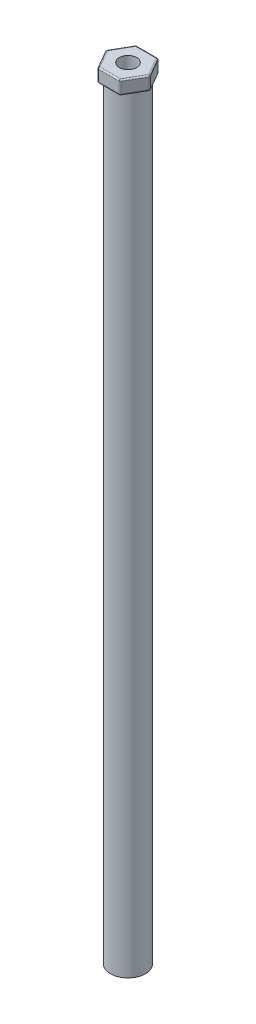
SolidWorks part; units mm, degrees
ref_plane "Front Plane" through (0, 0, 0) normal (0, 0, 1) x (1, 0, 0)
ref_plane "Top Plane" through (0, 0, 0) normal (0, 1, 0) x (1, 0, 0)
ref_plane "Right Plane" through (0, 0, 0) normal (1, 0, 0) x (0, 0, -1)
sketch "Sketch1" plane through (0, 0, 0) normal (0, 1, 0) x (1, 0, 0)
  circle A0 centre (0, 0) radius 6.35
  circle A1 centre (0, 0) radius 3.175
  dimension "D1" = 12.7
extrude "Boss-Extrude1" add sketch "Sketch1" along normal blind 279.4
ref_plane "Plane1" through (0, 139.7, 0) normal (0, 1, 0) x (1, 0, 0)
sketch "Sketch2" plane through (0, 279.4, 0) normal (0, 1, 0) x (1, 0, 0)
  line L1 (-8.0656, 0) -> (-4.0328, -6.985)
  line L2 (-4.0328, -6.985) -> (4.0328, -6.985)
  line L3 (4.0328, -6.985) -> (8.0656, 0)
  line L4 (8.0656, 0) -> (4.0328, 6.985)
  line L5 (4.0328, 6.985) -> (-4.0328, 6.985)
  line L6 (-4.0328, 6.985) -> (-8.0656, 0)
  circle A0 centre (0, 0) radius 6.985 construction
  circle A1 centre (0, 0) radius 3.175
  dimension "D1" = 13.97
extrude "Boss-Extrude2" add sketch "Sketch2" along normal blind 5
fillet "Fillet1" radius 0.5 18 edges at (6.0492, 279.4, -3.4925) (4.0328, 281.9, -6.985) (8.0656, 281.9, 0) (-4.0328, 281.9, -6.985) (-6.0492, 279.4, -3.4925) (-8.0656, 281.9, 0) (-6.0492, 279.4, 3.4925) (-4.0328, 281.9, 6.985) (0, 279.4, 6.985) (6.0492, 279.4, 3.4925) (4.0328, 281.9, 6.985) (6.0492, 284.4, 3.4925) (6.0492, 284.4, -3.4925) (0, 284.4, -6.985) (-6.0492, 284.4, -3.4925) (-6.0492, 284.4, 3.4925) (0, 284.4, 6.985) (0, 279.4, -6.985)
mirror "Mirror1" [suppressed] about plane through (0, 139.7, 0) normal (0, 1, 0)
